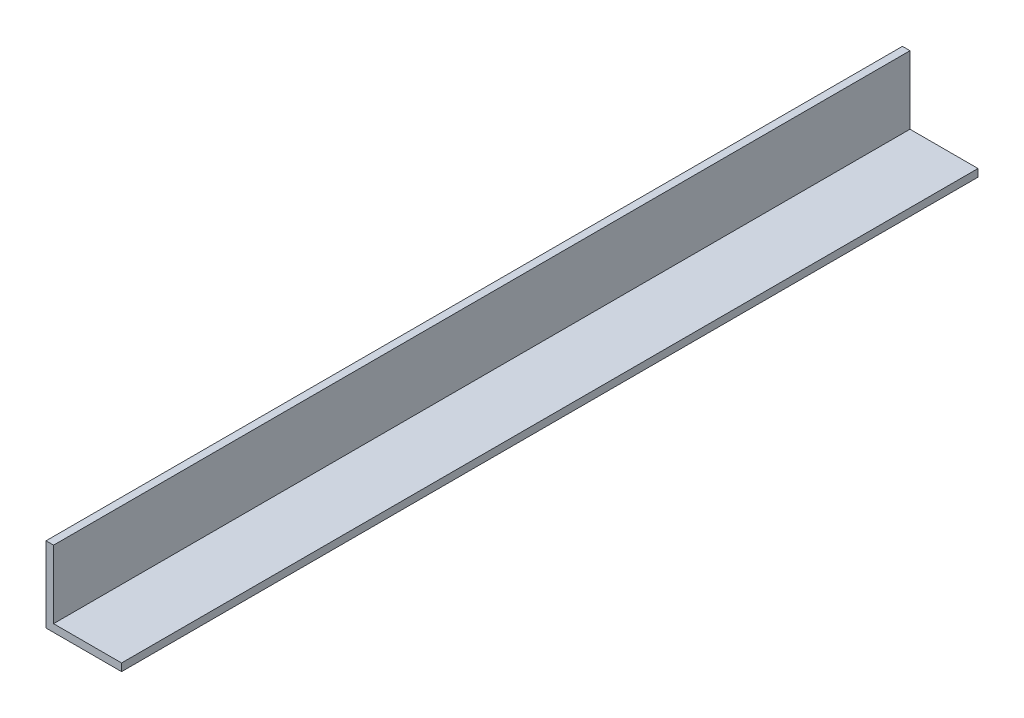
SolidWorks part; units mm, degrees
ref_plane "Piano frontale" through (0, 0, 0) normal (0, 0, 1) x (1, 0, 0)
ref_plane "Piano superiore" through (0, 0, 0) normal (0, 1, 0) x (1, 0, 0)
ref_plane "Piano destro" through (0, 0, 0) normal (1, 0, 0) x (0, 0, -1)
sketch "Schizzo1" plane through (0, 0, 0) normal (0, 0, 1) x (1, 0, 0)
  line L0 (0, 30) -> (0, 0)
  line L1 (0, 0) -> (30, 0)
  line L2 (30, 0) -> (30, 3)
  line L3 (30, 3) -> (3, 3)
  line L4 (3, 3) -> (3, 30)
  line L5 (3, 30) -> (0, 30)
  dimension "D1" = 3
  dimension "D2" = 3
  dimension "D3" = 30
  dimension "D4" = 30
extrude "Estrusione-Estrusione1" add sketch "Schizzo1" along normal blind 340
